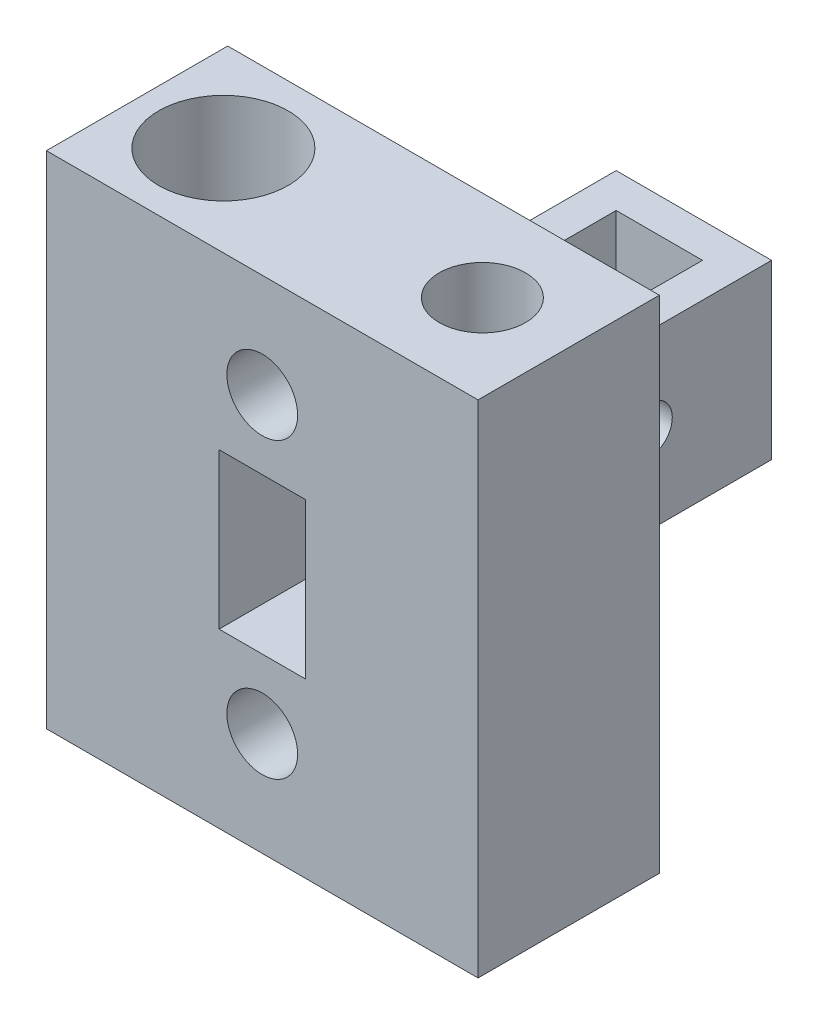
SolidWorks part; units mm, degrees
ref_plane "Front Plane" through (0, 0, 0) normal (0, 0, 1) x (1, 0, 0)
ref_plane "Top Plane" through (0, 0, 0) normal (0, 1, 0) x (1, 0, 0)
ref_plane "Right Plane" through (0, 0, 0) normal (1, 0, 0) x (0, 0, -1)
sketch "Sketch1" plane through (0, 0, 0) normal (0, 1, 0) x (1, 0, 0)
  line L1 (-25, 10.5) -> (25, 10.5)
  line L2 (-25, 10.5) -> (-25, -10.5)
  line L3 (-25, -10.5) -> (25, -10.5)
  line L4 (25, 10.5) -> (25, -10.5)
  line L5 (-25, 10.5) -> (25, -10.5) construction
  line L6 (-25, -10.5) -> (25, 10.5) construction
  point P0 (0, 0)
  dimension "D1" = 21
  dimension "D2" = 50
extrude "Boss-Extrude1" add sketch "Sketch1" along normal blind 58
sketch "Sketch3" plane through (0, 58, 0) normal (0, 1, 0) x (1, 0, 0)
  line L0 (-15, 0) -> (15, 0) construction
  circle A0 centre (-15, 0) radius 7.5
  dimension "D1" = 15
  dimension "D2" = 30
extrude "Cut-Extrude1" cut sketch "Sketch3" against normal blind 24 contours A0
sketch "Sketch4" plane through (0, 58, 0) normal (0, 1, 0) x (1, 0, 0)
  line L0 (-15, 0) -> (15, 0) construction
  circle A0 centre (15, 0) radius 5
  dimension "D1" = 10
extrude "Cut-Extrude2" cut sketch "Sketch4" against normal up to next
sketch "Sketch5" plane through (0, 0, 0) normal (0, -1, 0) x (1, 0, 0)
  circle A1 centre (-15, 0) radius 7.5
  circle A2 centre (-15, 0) radius 7.5
  dimension "D1" = 0
extrude "Cut-Extrude3" cut sketch "Sketch5" against normal blind 24
sketch "Sketch6" plane through (0, 0, 0) normal (0, -1, 0) x (1, 0, 0)
  circle A0 centre (-15, 0) radius 4.5
extrude "Cut-Extrude4" cut sketch "Sketch6" against normal up to next
sketch "Sketch7" plane through (0, 0, 10.5) normal (0, 0, 1) x (1, 0, 0)
  line L0 (0, 58) -> (0, 0) construction
  line L1 (-25, 58) -> (25, 58) construction
  line L2 (-25, 0) -> (25, 0) construction
  line L3 (-25, 29) -> (25, 29) construction
  line L4 (-25, 58) -> (-25, 0) construction
  line L5 (25, 58) -> (25, 0) construction
  circle A1 centre (0, 46) radius 4.1
  circle A2 centre (0, 12) radius 4.1
  point P24 (0, 12)
  dimension "D1" = 8.2
  dimension "D2" = 12
sketch "Sketch8" plane through (0, 0, 10.5) normal (0, 0, 1) x (1, 0, 0)
  line L0 (-25, 29) -> (25, 29) construction
  line L1 (-25, 58) -> (-25, 0) construction
  line L2 (25, 58) -> (25, 0) construction
  line L3 (0, 58) -> (0, 0) construction
  line L4 (-25, 58) -> (25, 58) construction
  line L6 (-5, 20) -> (5, 20)
  line L7 (-5, 20) -> (-5, 38)
  line L8 (-5, 38) -> (5, 38)
  line L9 (5, 20) -> (5, 38)
  line L10 (-5, 20) -> (5, 38) construction
  line L11 (-5, 38) -> (5, 20) construction
  point P11 (0, 29)
  dimension "D1" = 18
  dimension "D2" = 10
extrude "Cut-Extrude5" cut sketch "Sketch8" against normal up to next
sketch "Sketch10" plane through (0, 0, -10.5) normal (0, 0, -1) x (-1, 0, 0)
  line L0 (-25, 29) -> (25, 29) construction
  line L1 (-25, 58) -> (-25, 0) construction
  line L2 (25, 58) -> (25, 0) construction
  line L3 (0, 58) -> (0, 0) construction
  line L4 (-25, 58) -> (25, 58) construction
extrude "Cut-Extrude6" cut sketch "Sketch7" against normal blind 15
sketch "Sketch11" plane through (0, 0, -10.5) normal (0, 0, -1) x (-1, 0, 0)
  line L0 (-25, 29) -> (25, 29) construction
  line L1 (9, 39) -> (5, 39)
  line L2 (9, 39) -> (9, 19)
  line L3 (9, 19) -> (5, 19)
  line L4 (5, 39) -> (5, 19)
  line L5 (9, 39) -> (5, 19) construction
  line L6 (9, 19) -> (5, 39) construction
  line L7 (0, 58) -> (0, 0) construction
  line L8 (0, 58) -> (0, 0)
  line L9 (-9, 19) -> (-5, 19)
  line L10 (-5, 39) -> (-5, 19)
  line L11 (-9, 39) -> (-5, 39)
  line L12 (-9, 39) -> (-9, 19)
  point P0 (7, 29)
  line M7 (-5, 20) -> (-5, 38)
  line M9 (5, 38) -> (5, 20)
  dimension "D1" = 5
  dimension "D2" = 4
  dimension "D3" = 20
extrude "Boss-Extrude2" add sketch "Sketch11" along normal blind 25 contours L1 L4 L3 L2 M9 | L11 L12 L9 L10 M7
sketch "Sketch12" plane through (0, 0, -35.5) normal (0, 0, -1) x (-1, 0, 0)
  line L1 (9, 19) -> (-9, 19)
  line L2 (9, 19) -> (9, 39)
  line L3 (9, 39) -> (-9, 39)
  line L4 (-9, 19) -> (-9, 39)
extrude "Boss-Extrude3" add sketch "Sketch12" along normal blind 4
sketch "Sketch13" plane through (9, 0, 0) normal (1, 0, 0) x (0, 0, -1)
  line L3 (10.5, 29) -> (39.5, 29) construction
  line L4 (10.5, 39) -> (10.5, 19) construction
  line L5 (39.5, 39) -> (39.5, 19) construction
  line L6 (16.25, 29) -> (25.25, 29) construction
  line L7 (16.25, 31.75) -> (25.25, 31.75)
  line L8 (16.25, 26.25) -> (25.25, 26.25)
  arc A0 (16.25, 31.75) -> (16.25, 26.25) centre (16.25, 29) ccw
  arc A1 (25.25, 26.25) -> (25.25, 31.75) centre (25.25, 29) ccw
  point P0 (16.1081, 29)
  point P1 (13.5, 29)
  point P14 (20.75, 29)
  dimension "D1" = 5.5
  dimension "D2" = 3
  dimension "D3" = 9
extrude "Cut-Extrude7" cut sketch "Sketch13" against normal through all
